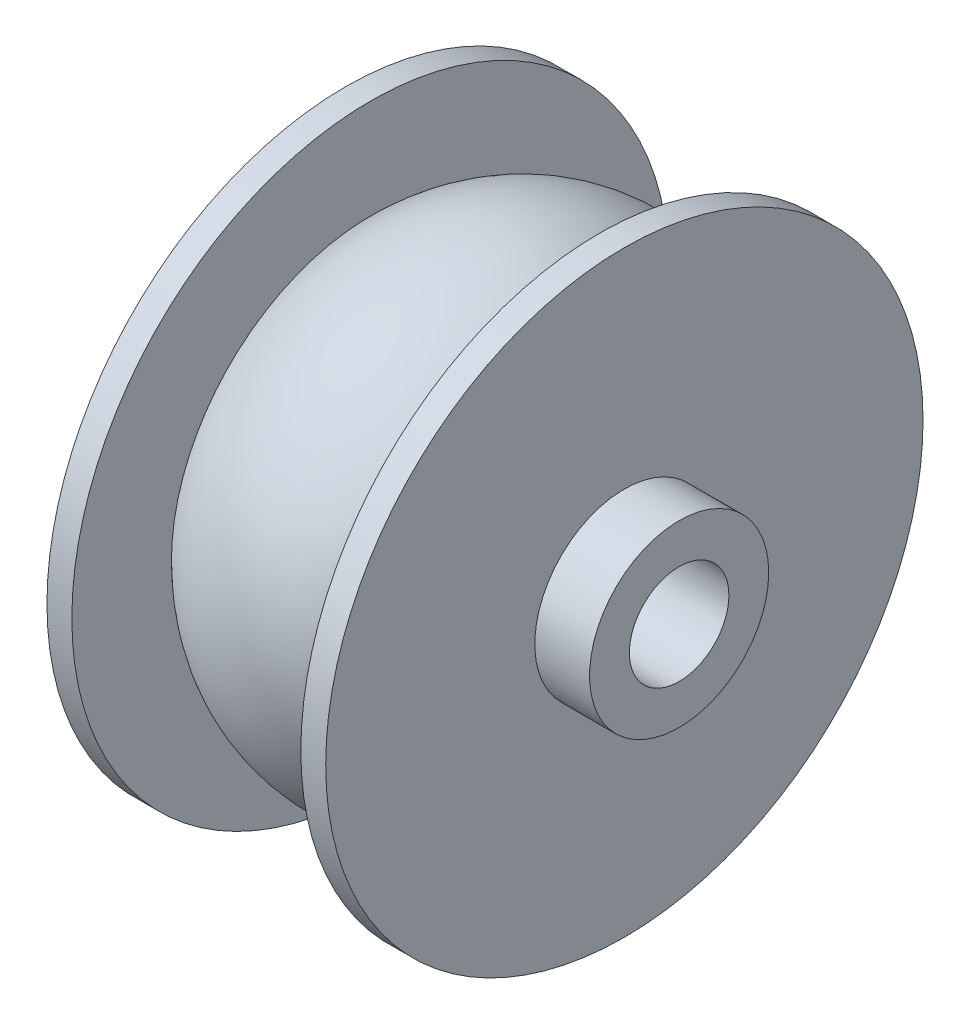
SolidWorks part; units mm, degrees
material "PE Low Density Film"
ref_plane "Front Plane" through (0, 0, 0) normal (0, 0, 1) x (1, 0, 0)
ref_plane "Top Plane" through (0, 0, 0) normal (0, 1, 0) x (1, 0, 0)
ref_plane "Right Plane" through (0, 0, 0) normal (1, 0, 0) x (0, 0, -1)
sketch "Sketch1" plane through (0, 0, 0) normal (1, 0, 0) x (0, 0, -1)
  circle A0 centre (0, 0) radius 6
  dimension "D1" = 12
extrude "Boss-Extrude1" add sketch "Sketch1" along normal blind 5.6
sketch "Sketch2" plane through (5.6, 0, 0) normal (1, 0, 0) x (0, 0, -1)
  circle A0 centre (0, 0) radius 1
  dimension "D1" = 2
extrude "Cut-Extrude1" cut sketch "Sketch2" against normal blind 6.7
sketch "Sketch3" plane through (5.6, 0, 0) normal (1, 0, 0) x (0, 0, -1)
  circle A0 centre (0, 0) radius 1.8
  circle A1 centre (0, 0) radius 1 construction
  circle A2 centre (0, 0) radius 1
  dimension "D1" = 3.6
extrude "Boss-Extrude2" add sketch "Sketch3" along normal blind 1.1
sketch "Sketch4" plane through (0, 0, 0) normal (0, 0, 1) x (1, 0, 0)
  line L0 (0.5, 6) -> (0.5, 4)
  line L1 (5.6, 6) -> (0, 6) construction
  line L2 (0.5, 4) -> (5.1, 4)
  line L3 (5.1, 4) -> (5.1, 6)
  line L4 (0, 6) -> (0, -6) construction
  line L5 (5.6, -6) -> (5.6, 6) construction
  line L6 (0, 0) -> (5.6, 0) construction
  line L7 (5.6, -1.8) -> (5.6, 1.8) construction
  line L8 (0.5, 6) -> (5.1, 6)
  arc A0 (0.5, 4) -> (5.1, 4) centre (2.8, 1.7) cw
  dimension "D1" = 0.5
  dimension "D2" = 2
  dimension "D3" = 0.5
revolve "Cut-Revolve1" cut sketch "Sketch4" angle 360 about L6
